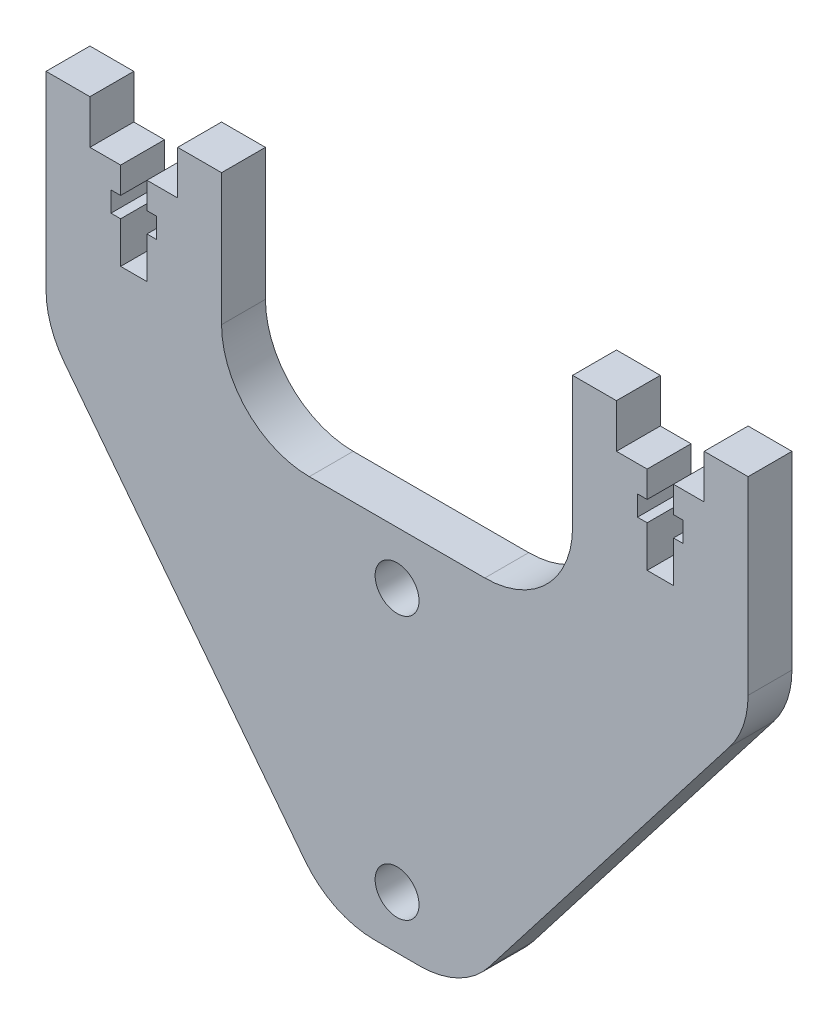
SolidWorks part; units mm, degrees
ref_plane "Plan de face" through (0, 0, 0) normal (0, 0, 1) x (1, 0, 0)
ref_plane "Plan de dessus" through (0, 0, 0) normal (0, 1, 0) x (1, 0, 0)
ref_plane "Plan de droite" through (0, 0, 0) normal (1, 0, 0) x (0, 0, -1)
sketch "Esquisse1" plane through (0, 0, 0) normal (0, 0, 1) x (1, 0, 0)
  line L0 (0, 0) -> (40, 0) construction
  line L1 (0, 0) -> (0, 31.2901) construction
  line L2 (-40, 0) -> (-40, -20)
  line L3 (-40, -20) -> (-7.5, -62)
  line L4 (40, -20) -> (40, 0)
  line L5 (-20, 0) -> (-20, -20)
  line L6 (-20, -20) -> (20, -20)
  line L7 (20, -20) -> (20, 0)
  line L8 (0, -20) -> (0, -62) construction
  line L9 (-7.5, -62) -> (7.5, -62)
  line L10 (7.5, -62) -> (40, -20)
  line L11 (-40, -20) -> (40, -20) construction
  circle A0 centre (0, -26) radius 2.5
  circle A2 centre (0, -56) radius 2.5
  line B0 (32.6, -3) -> (32.6, -5.3)
  line B1 (28.5, -5.3) -> (28.5, -10)
  line B2 (31.5, -10) -> (31.5, -5.3)
  line B3 (32.6, -5.3) -> (31.5, -5.3)
  line B4 (30, 0) -> (30, -11.2208) construction
  line B5 (31.5, 0) -> (35, 0)
  line B6 (35, 5) -> (40, 5)
  line B7 (40, 5) -> (40, 0)
  line B8 (35, 5) -> (35, 0)
  line B9 (28.5, 0) -> (25, 0)
  line B10 (25, 0) -> (25, 5)
  line B11 (25, 5) -> (20, 5)
  line B12 (20, 5) -> (20, 0)
  line B13 (31.5, 0) -> (28.5, 0) construction
  line B14 (28.5, 0) -> (28.5, -3)
  line B15 (28.5, -5.3) -> (27.4, -5.3)
  line B16 (27.4, -3) -> (28.5, -3)
  line B17 (28.5, -10) -> (31.5, -10)
  line B18 (31.5, -3) -> (32.6, -3)
  line B19 (27.4, -5.3) -> (27.4, -3)
  line B20 (31.5, -3) -> (31.5, 0)
  line B21 (30, -10) -> (30, 0) construction
  line B22 (-32.6, -3) -> (-32.6, -5.3)
  line B23 (-28.5, -5.3) -> (-28.5, -10)
  line B24 (-31.5, -10) -> (-31.5, -5.3)
  line B25 (-32.6, -5.3) -> (-31.5, -5.3)
  line B26 (-30, 0) -> (-30, -11.2208) construction
  line B27 (-31.5, 0) -> (-35, 0)
  line B28 (-35, 5) -> (-40, 5)
  line B29 (-40, 5) -> (-40, 0)
  line B30 (-35, 5) -> (-35, 0)
  line B31 (-28.5, 0) -> (-25, 0)
  line B32 (-25, 0) -> (-25, 5)
  line B33 (-25, 5) -> (-20, 5)
  line B34 (-20, 5) -> (-20, 0)
  line B35 (-31.5, 0) -> (-28.5, 0) construction
  line B36 (-28.5, 0) -> (-28.5, -3)
  line B37 (-28.5, -5.3) -> (-27.4, -5.3)
  line B38 (-27.4, -3) -> (-28.5, -3)
  line B39 (-28.5, -10) -> (-31.5, -10)
  line B40 (-31.5, -3) -> (-32.6, -3)
  line B41 (-27.4, -5.3) -> (-27.4, -3)
  line B42 (-31.5, -3) -> (-31.5, 0)
  line B43 (-30, -10) -> (-30, 0) construction
  dimension "D5" = 5
  dimension "D1" = 60
  dimension "D2" = 30
  dimension "D3" = 20
  dimension "D4" = 6
  dimension "D6" = 6
  dimension "D7" = 15
sketch_block_instance "Insert M3 plots ep 5mm-1"
sketch_block "Insert M3 plots ep 5mm" parameters "D1"=10, "D2"=5, "D3"=5
sketch_block_instance "Decoupe Insert M3-4"
sketch_block "Decoupe Insert M3" parameters "D1"=5.2, "D2"=3, "D3"=2.3, "D4"=3, "D5"=10
sketch_block_instance "Insert M3 plots ep 5mm-3"
extrude "Boss.-Extru.1" add sketch "Esquisse1" along normal blind 5
fillet "Congé1" radius 10 6 edges at (20, -20, 2.5) (-20, -20, 2.5) (-40, -20, 2.5) (40, -20, 2.5) (-7.5, -62, 2.5) (7.5, -62, 2.5)
